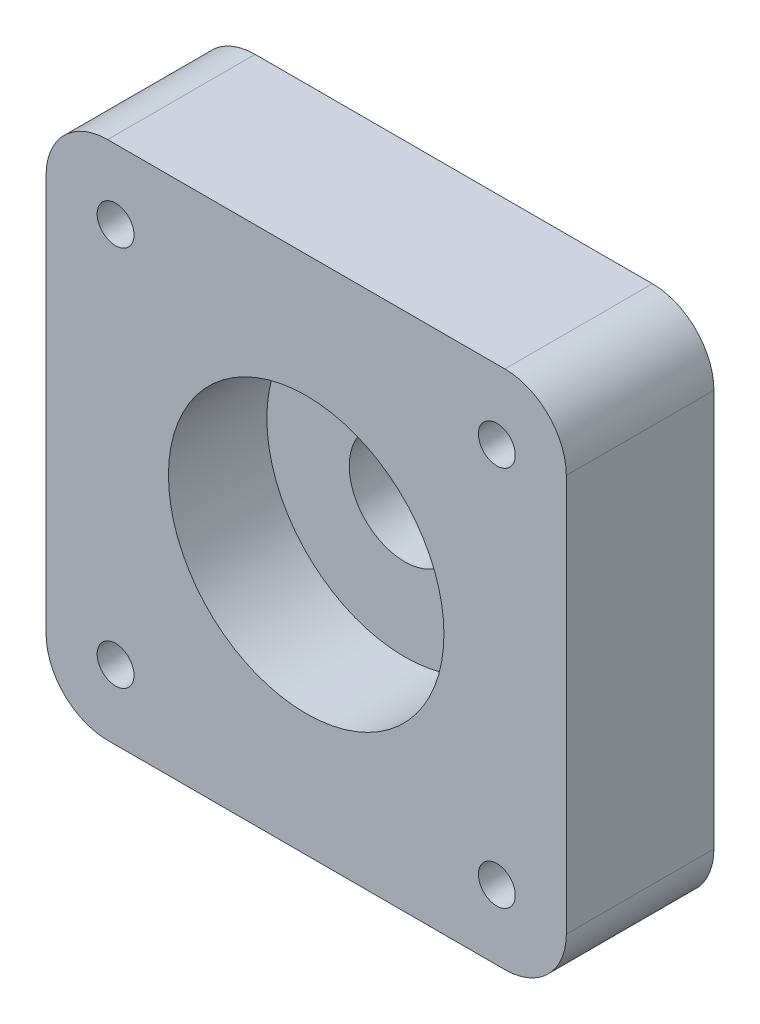
SolidWorks part; units mm, degrees
ref_plane "Alzado" through (0, 0, 0) normal (0, 0, 1) x (1, 0, 0)
ref_plane "Planta" through (0, 0, 0) normal (0, 1, 0) x (1, 0, 0)
ref_plane "Vista lateral" through (0, 0, 0) normal (1, 0, 0) x (0, 0, -1)
sketch "Croquis1" plane through (0, 0, 0) normal (0, 0, 1) x (1, 0, 0)
  line L0 (0, 25.4786) -> (0, -27.3465) construction
  line L1 (-21.15, -21.15) -> (21.15, -21.15)
  line L2 (-21.15, -21.15) -> (-21.15, 21.15)
  line L3 (-21.15, 21.15) -> (21.15, 21.15)
  line L4 (21.15, -21.15) -> (21.15, 21.15)
  line L5 (-21.15, -21.15) -> (21.15, 21.15) construction
  line L6 (-21.15, 21.15) -> (21.15, -21.15) construction
  line L7 (-15.5, 15.5) -> (-15.5, -15.5) construction
  line L8 (15.5, 15.5) -> (15.5, -15.5) construction
  circle A0 centre (-15.5, 15.5) radius 1.5
  circle A1 centre (-15.5, -15.5) radius 1.5
  circle A2 centre (15.5, -15.5) radius 1.5
  circle A3 centre (15.5, 15.5) radius 1.5
  point P0 (0, 0)
  dimension "D3" = 3
  dimension "D1" = 42.3
  dimension "D2" = 42.3
  dimension "D4" = 15.5
extrude "Saliente-Extruir1" add sketch "Croquis1" along normal mid plane 12
fillet "Redondeo1" radius 5 4 edges at (-21.15, 21.15, 0) (-21.15, -21.15, 0) (21.15, -21.15, 0) (21.15, 21.15, 0)
sketch "Croquis2" plane through (0, 0, 6) normal (0, 0, 1) x (1, 0, 0)
  circle A0 centre (0, 0) radius 11.2
  dimension "D1" = 22.4
extrude "Cortar-Extruir1" cut sketch "Croquis2" against normal blind 8
sketch "Croquis3" plane through (0, 0, -6) normal (0, 0, -1) x (-1, 0, 0)
  circle A0 centre (0, 0) radius 4.5
  dimension "D1" = 9
extrude "Cortar-Extruir2" cut sketch "Croquis3" against normal blind 10
